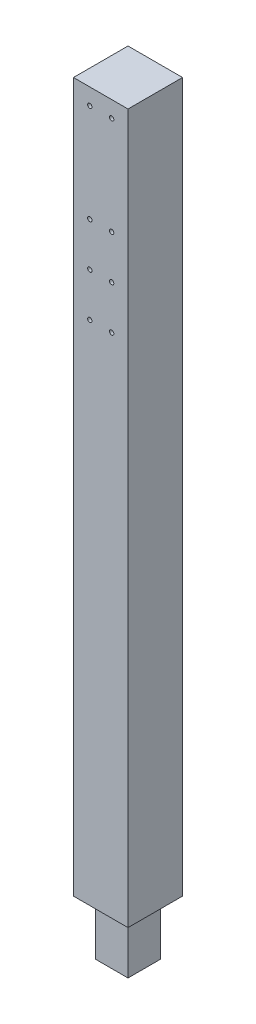
SolidWorks part; units mm, degrees
material "Mahogany"
ref_plane "Plan de face" through (0, 0, 0) normal (0, 0, 1) x (1, 0, 0)
ref_plane "Plan de dessus" through (0, 0, 0) normal (0, 1, 0) x (1, 0, 0)
ref_plane "Plan de droite" through (0, 0, 0) normal (1, 0, 0) x (0, 0, -1)
sketch "Sketch2" plane through (0, 0, 0) normal (0, 1, 0) x (1, 0, 0)
  line L1 (0, 0) -> (25, 0)
  line L2 (0, 0) -> (0, 25)
  line L3 (0, 25) -> (25, 25)
  line L4 (25, 0) -> (25, 25)
  dimension "D1" = 25
  dimension "D2" = 25
extrude "Boss-Extrude1" add sketch "Sketch2" along normal blind 350
sketch "Sketch3" plane through (0, 0, 0) normal (0, 0, 1) x (1, 0, 0)
  line L0 (12.5, 350) -> (12.5, 0) construction
  line L1 (7.5, 350) -> (7.5, 0) construction
  line L4 (0, 0) -> (25, 0)
  line L5 (25, 0) -> (25, 350)
  line L6 (25, 350) -> (0, 350)
  line L7 (0, 350) -> (0, 0)
  line L8 (0, 0) -> (25, 0)
  line L10 (25, 350) -> (0, 350)
  circle A0 centre (7.5, 342.5) radius 1
  circle A1 centre (7.5, 297.5) radius 1
  circle A2 centre (7.5, 277.5) radius 1
  circle A3 centre (7.5, 257.5) radius 1
  circle A4 centre (17.5, 342.5) radius 1
  circle A5 centre (17.5, 297.5) radius 1
  circle A6 centre (17.5, 277.5) radius 1
  circle A7 centre (17.5, 257.5) radius 1
  dimension "D3" = 7.5
  dimension "D4" = 2
  dimension "D5" = 2
  dimension "D6" = 45
  dimension "D7" = 2
  dimension "D8" = 2
  dimension "D9" = 20
  dimension "D10" = 20
  dimension "D2" = 5
  dimension "D1" = 0
extrude "Cut-Extrude1" cut sketch "Sketch3" against normal through all contours A0 | A4 | A1 | A5 | A2 | A6 | A7 | A3
sketch "Sketch4" plane through (0, 0, 0) normal (-1, 0, 0) x (0, 0, 1)
  line L0 (-25, 25) -> (-20, 25)
  line L1 (-12.5, 0) -> (-12.5, 350) construction
  line L2 (-20, 25) -> (-20, 0)
  line L3 (-25, 350) -> (0, 350) construction
  line L4 (-25, 0) -> (0, 0)
  line L5 (0, 0) -> (0, 350)
  line L6 (0, 350) -> (-25, 350)
  line L7 (-25, 350) -> (-25, 0)
  line L8 (-25, 0) -> (0, 0)
  line L11 (-25, 25) -> (-25, 0)
  line L12 (-25, 350) -> (0, 350)
  line L13 (0, 25) -> (0, 0)
  line L14 (0, 25) -> (-5, 25)
  line L15 (-5, 25) -> (-5, 0)
  point P8 (-19.5061, 20)
  point P9 (0, 0)
  line M9 (-25, 0) -> (0, 0)
  line M10 (0, 0) -> (0, 350)
  line M12 (-25, 350) -> (-25, 0)
  dimension "D2" = 25
  dimension "D3" = 7.5
  dimension "D4" = 5
  dimension "D1" = 0
extrude "Cut-Extrude2" cut sketch "Sketch4" against normal through all and the other way through all contours L2 L0 M12 M9 | L14 L15 L8 M10
sketch "Sketch5" plane through (0, 0, -20) normal (0, 0, -1) x (-1, 0, 0)
  line L0 (-20, 25) -> (-20, 0)
  line L1 (-12.5, 25) -> (-12.5, 0) construction
  line L2 (-5, 25) -> (-5, 0)
  line L4 (0, 0) -> (0, 25)
  line L5 (0, 25) -> (-25, 25)
  line L6 (-25, 25) -> (-25, 0)
  line L7 (-25, 0) -> (0, 0)
  line L8 (0, 0) -> (0, 25)
  line L9 (0, 25) -> (-25, 25)
  line L10 (-25, 25) -> (-25, 0)
  line L11 (-25, 0) -> (0, 0)
  line M7 (0, 0) -> (0, 25)
  line M8 (0, 25) -> (-25, 25)
  line M9 (-25, 25) -> (-25, 0)
  line M10 (-25, 0) -> (0, 0)
  dimension "D2" = 5
  dimension "D1" = 0
extrude "Cut-Extrude3" cut sketch "Sketch5" against normal through all contours L0 M8 M9 M10 | L2 M8 M10 M7
